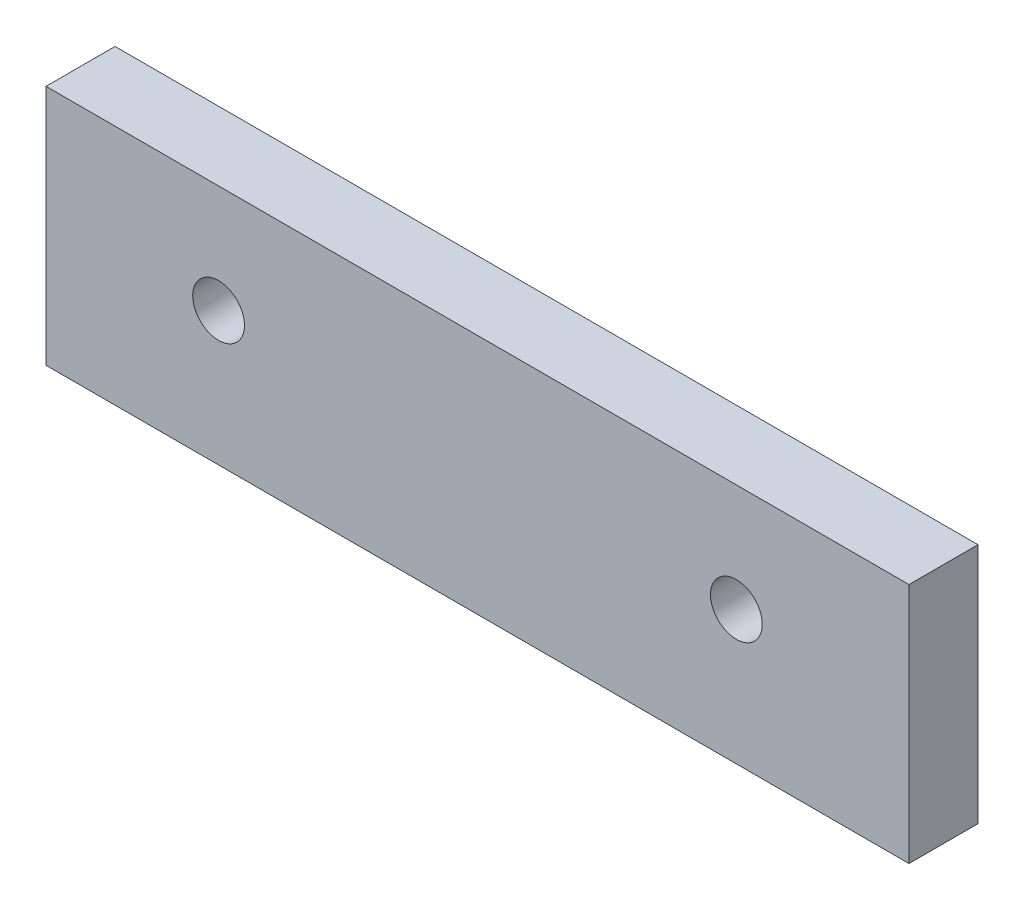
SolidWorks part; units mm, degrees
material "201 Annealed Stainless Steel (SS)"
ref_plane "Front Plane" through (0, 0, 0) normal (0, 0, 1) x (1, 0, 0)
ref_plane "Top Plane" through (0, 0, 0) normal (0, 1, 0) x (1, 0, 0)
ref_plane "Right Plane" through (0, 0, 0) normal (1, 0, 0) x (0, 0, -1)
sketch "Sketch1" plane through (0, 0, 0) normal (0, 0, 1) x (1, 0, 0)
  line L1 (-50, 14) -> (50, 14)
  line L2 (-50, 14) -> (-50, -14)
  line L3 (-50, -14) -> (50, -14)
  line L4 (50, 14) -> (50, -14)
  line L5 (-50, 14) -> (50, -14) construction
  line L6 (-50, -14) -> (50, 14) construction
  point P0 (0, 0)
  dimension "D1" = 28
  dimension "D2" = 100
extrude "Boss-Extrude1" add sketch "Sketch1" along normal blind 8
sketch "Sketch2" plane through (0, 0, 0) normal (0, 0, -1) x (-1, 0, 0)
  line L0 (0, -1000) -> (0, 49000) construction
  line L1 (-50, 14) -> (50, 14) construction
  circle A0 centre (-30, 1.5) radius 6
  circle A1 centre (30, 1.5) radius 6
  dimension "D3" = 12
  dimension "D1" = 60
  dimension "D2" = 12.5
hole_wizard "CSK for M6 Countersunk Flat Head Screw1" positions "Sketch3" profile "Sketch4" countersink size "M6" standard "ISO" end condition through all
sketch "Sketch3" plane through (0, 0, 0) normal (0, 0, -1) x (-1, 0, 0)
  point P0 (30, 1.5)
  point P3 (-30, 1.5)
sketch "Sketch4" plane through (-30, 1.5, 0) normal (1, 0, 0) x (0, 1, 0)
  line L0 (0, 0) -> (0, 8)
  line L1 (0, 8) -> (3, 8)
  line L2 (3, 8) -> (3, 3)
  line L3 (3, 3) -> (6, 0)
  line L5 (6, 0) -> (0, 0)
  line L6 (-3, 3) -> (-6, 0) construction
  line L11 (0, -6.35) -> (0, 107.95) construction
  dimension "Thru Hole Dia." = 6
  dimension "Thru Hole Depth" = 8
  dimension "Near C'Sink Dia." = 12
  dimension "Near C'Sink Angle" = 90
